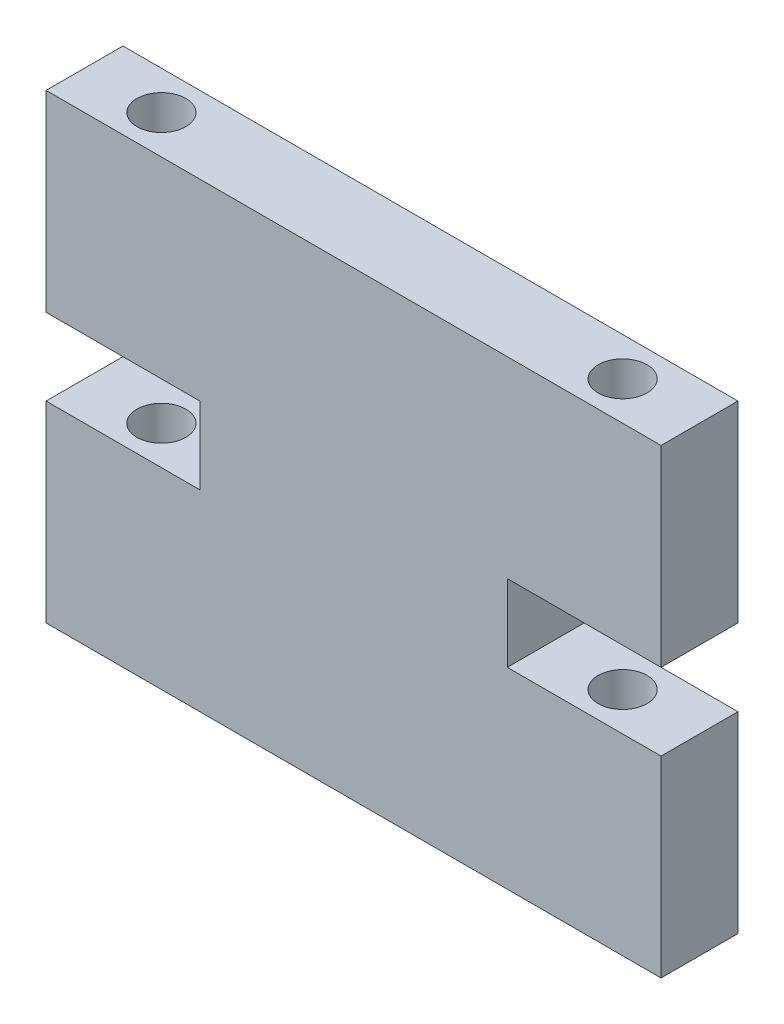
SolidWorks part; units mm, degrees
ref_plane "Front Plane" through (0, 0, 0) normal (0, 0, 1) x (1, 0, 0)
ref_plane "Top Plane" through (0, 0, 0) normal (0, 1, 0) x (1, 0, 0)
ref_plane "Right Plane" through (0, 0, 0) normal (1, 0, 0) x (0, 0, -1)
sketch "Sketch1" plane through (0, 0, 0) normal (0, 0, 1) x (1, 0, 0)
  line L0 (55, 0) -> (-55, 0) construction
  line L1 (-15, 15) -> (15, 15)
  line L2 (-10, 2.5) -> (-10, -2.5)
  line L3 (-15, -15) -> (15, -15)
  line L4 (10, 2.5) -> (10, -2.5)
  line L5 (-15, 15) -> (15, -15) construction
  line L6 (-15, -15) -> (15, 15) construction
  line L7 (-15, 15) -> (-20, 15)
  line L9 (-10, 2.5) -> (-20, 2.5)
  line L10 (-20, 15) -> (-20, 2.5)
  line L11 (-15, 15) -> (-20, 2.5) construction
  line L12 (-10, 2.5) -> (-20, 15) construction
  line L13 (-15, -15) -> (-20, -15)
  line L14 (-20, -15) -> (-20, -2.5)
  line L15 (-10, -2.5) -> (-20, -2.5)
  line L16 (0, -55) -> (0, 55) construction
  line L17 (15, -15) -> (20, -15)
  line L18 (20, -15) -> (20, -2.5)
  line L19 (10, -2.5) -> (20, -2.5)
  line L20 (10, 2.5) -> (20, 2.5)
  line L21 (20, 15) -> (20, 2.5)
  line L22 (15, 15) -> (20, 15)
  point P0 (0, 0)
  point P9 (-16.6667, 10.8333)
  dimension "D1" = 30
  dimension "D2" = 30
  dimension "D3" = 5
  dimension "D4" = 12.5
extrude "Boss-Extrude1" add sketch "Sketch1" along normal blind 5
sketch "Sketch2" plane through (0, 15, 0) normal (0, 1, 0) x (1, 0, 0)
  line L0 (-20, -2.5) -> (20, -2.5) construction
  line L1 (-20, -5) -> (-20, 0) construction
  line L2 (20, -5) -> (20, 0) construction
  line L3 (-10, 0) -> (-10, -5) construction
  line L4 (20, 0) -> (-20, 0) construction
  line L5 (20, -5) -> (-20, -5) construction
  line L6 (-10, 0) -> (-20, 0) construction
  line L7 (-15, 0) -> (-15, -5) construction
  circle A0 centre (-15, -2.5) radius 1.5918
  point P18 (-30, -5)
  point P19 (-15, -2.5)
  dimension "D1" = 3.1836
  dimension "D2" = 10
extrude "Cut-Extrude1" cut sketch "Sketch2" against normal through all
mirror "Mirror1" about plane through (0, 0, 0) normal (1, 0, 0) of "Cut-Extrude1"
